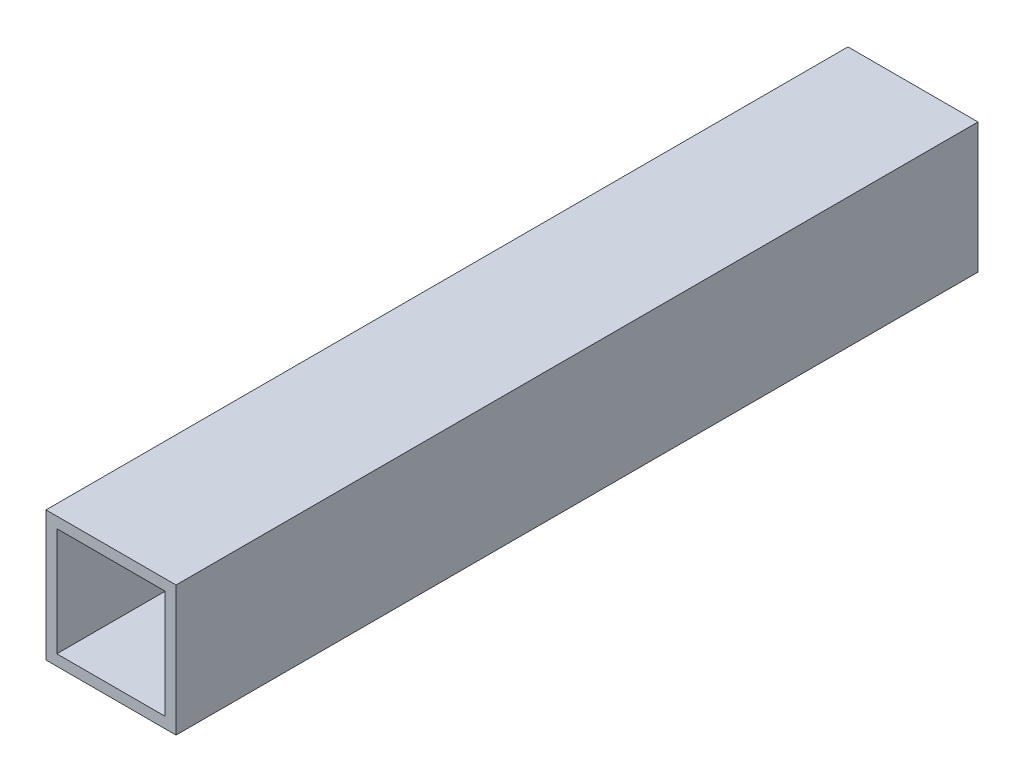
SolidWorks part; units mm, degrees
ref_plane "前视基准面" through (0, 0, 0) normal (0, 0, 1) x (1, 0, 0)
ref_plane "上视基准面" through (0, 0, 0) normal (0, 1, 0) x (1, 0, 0)
ref_plane "右视基准面" through (0, 0, 0) normal (1, 0, 0) x (0, 0, -1)
sketch "草图1" plane through (0, 0, 0) normal (0, 0, 1) x (1, 0, 0)
  line L0 (-12, 12) -> (12, 12)
  line L1 (-10, 10) -> (10, 10)
  line L2 (-10, 10) -> (-10, -10)
  line L3 (-10, -10) -> (10, -10)
  line L4 (10, 10) -> (10, -10)
  line L5 (-10, 10) -> (10, -10) construction
  line L6 (-10, -10) -> (10, 10) construction
  line L7 (12, 12) -> (12, -12)
  line L8 (-12, -12) -> (12, -12)
  line L9 (-12, 12) -> (-12, -12)
  point P0 (0, 0)
  dimension "D1" = 20
  dimension "D2" = 20
  dimension "D3" = 2
extrude "凸台-拉伸1" add sketch "草图1" along normal blind 148
